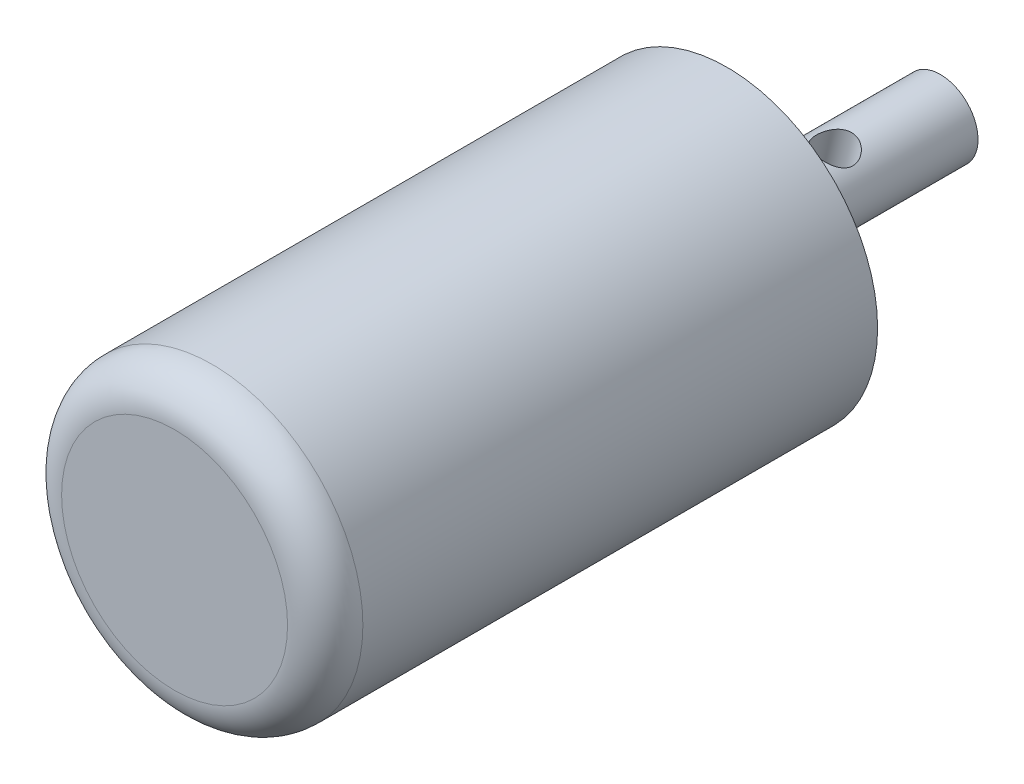
SolidWorks part; units mm, degrees
ref_plane "前视基准面" through (0, 0, 0) normal (0, 0, 1) x (1, 0, 0)
ref_plane "上视基准面" through (0, 0, 0) normal (0, 1, 0) x (1, 0, 0)
ref_plane "右视基准面" through (0, 0, 0) normal (1, 0, 0) x (0, 0, -1)
sketch "草图1" plane through (0, 0, 0) normal (0, 0, 1) x (1, 0, 0)
  circle A0 centre (0, 0) radius 12
  dimension "D1" = 24
extrude "凸台-拉伸1" add sketch "草图1" along normal blind 44
sketch "草图2" plane through (0, 0, 0) normal (0, 0, -1) x (-1, 0, 0)
  circle A0 centre (0, 0) radius 6.5
  dimension "D1" = 13
extrude "凸台-拉伸2" add sketch "草图2" along normal blind 2
sketch "草图3" plane through (0, 0, -2) normal (0, 0, -1) x (-1, 0, 0)
  circle A0 centre (0, 0) radius 3
  dimension "D1" = 6
extrude "凸台-拉伸3" add sketch "草图3" along normal blind 15
sketch "草图4" plane through (0, 0, 0) normal (0, 0, -1) x (-1, 0, 0)
  circle A0 centre (0, 0) radius 9 construction
  circle A1 centre (0, -9) radius 1.5
  circle A2 centre (0, 0) radius 9 construction
  circle A3 centre (-7.7942, 4.5) radius 1.5
  circle A4 centre (0, 0) radius 9 construction
  circle A5 centre (7.7942, 4.5) radius 1.5
  point P13 (0, 0)
  dimension "D1" = 18
  dimension "D2" = 3
  dimension "D3" = 3
extrude "切除-拉伸1" cut sketch "草图4" against normal blind 5
sketch "草图5" plane through (0, 0, -17) normal (0, 0, -1) x (-1, 0, 0)
  line L0 (2.161, -2.0809) -> (-1.0767, -2.8001)
  circle A0 centre (0, 0) radius 3 construction
  arc A1 (-1.0767, -2.8001) -> (2.161, -2.0809) centre (0, 0) ccw
  point P4 (0.5421, -2.4405)
  point P5 (0, 0)
  dimension "D1" = 2.5
extrude "切除-拉伸2" cut sketch "草图5" against normal blind 11.5
sketch "草图6" plane through (-0.5421, -2.4405, 0) normal (-0.2169, -0.9762, 0) x (-0.9762, 0.2169, 0)
  line L1 (1.6583, 17) -> (-1.6583, 17) construction
  circle A0 centre (0, 8) radius 1.5
  point P5 (0, 17)
  dimension "D1" = 3
  dimension "D2" = 9
extrude "切除-拉伸3" cut sketch "草图6" against normal through all
fillet "圆角1" radius 3 1 edges at (12, 0, 44)
sketch "草图7" plane through (0, 0, -17) normal (0, 0, -1) x (-1, 0, 0)
  point P0 (0, 0)
